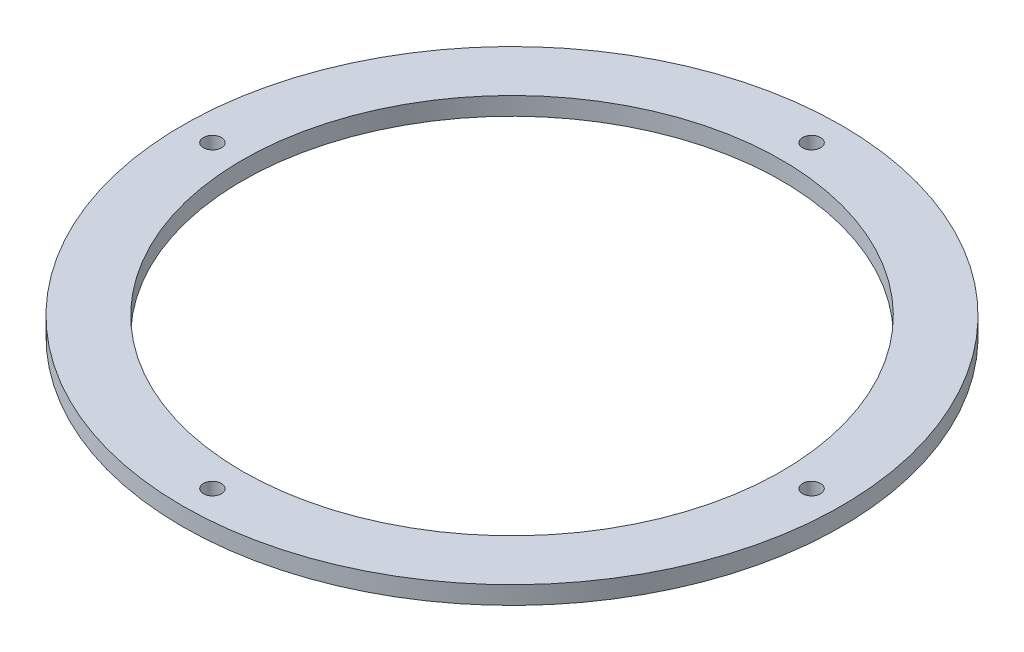
SolidWorks part; units mm, degrees
ref_plane "前视基准面" through (0, 0, 0) normal (0, 0, 1) x (1, 0, 0)
ref_plane "上视基准面" through (0, 0, 0) normal (0, 1, 0) x (1, 0, 0)
ref_plane "右视基准面" through (0, 0, 0) normal (1, 0, 0) x (0, 0, -1)
other "Configuration Table"
sketch "草图1" plane through (0, 0, 0) normal (0, 1, 0) x (1, 0, 0)
  circle A0 centre (0, 0) radius 45
  circle A1 centre (0, 0) radius 50 construction
  circle A2 centre (0, 0) radius 55
  circle A3 centre (0, 50) radius 1.5
  circle A4 centre (0, 0) radius 45
  circle A5 centre (50, 0) radius 1.5
  circle A6 centre (0, 0) radius 45
  circle A7 centre (0, -50) radius 1.5
  circle A8 centre (0, 0) radius 45
  circle A9 centre (-50, 0) radius 1.5
  point P19 (0, 0)
  dimension "D1" = 90
  dimension "D2" = 100
  dimension "D3" = 110
  dimension "D4" = 3
  dimension "D5" = 4
extrude "凸台-拉伸1" add sketch "草图1" along normal blind 3 contours A2 A9 A7 A5 A3 A0
